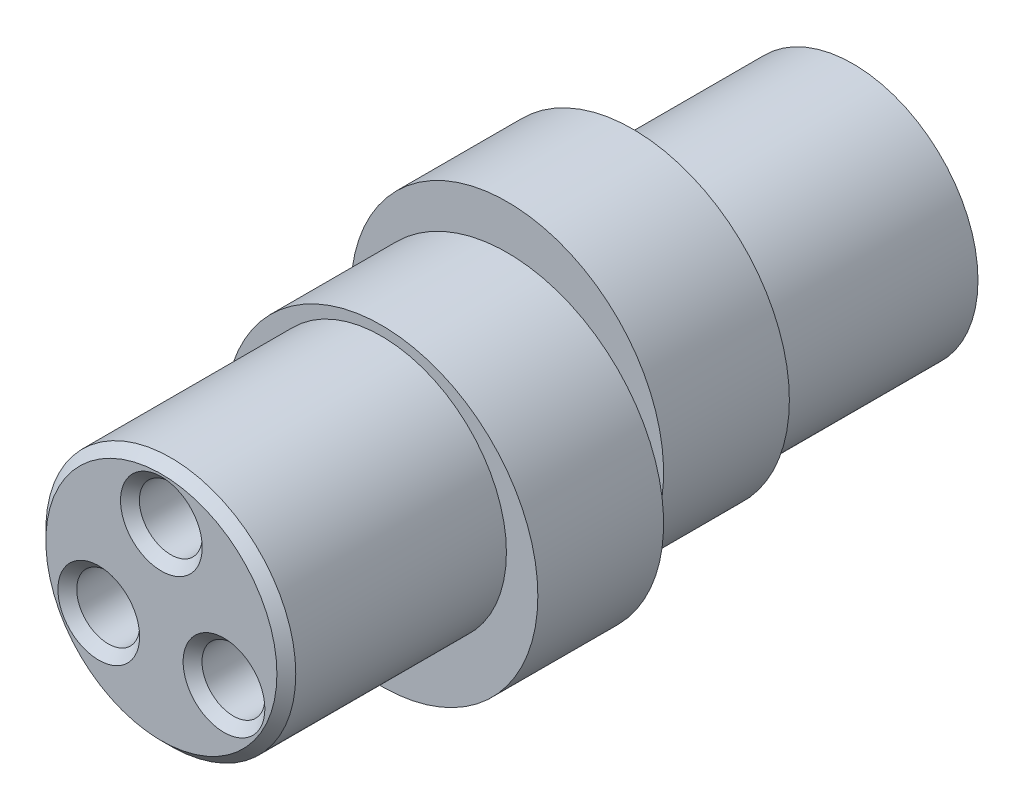
SolidWorks part; units mm, degrees
ref_plane "Front Plane" through (0, 0, 0) normal (0, 0, 1) x (1, 0, 0)
ref_plane "Top Plane" through (0, 0, 0) normal (0, 1, 0) x (1, 0, 0)
ref_plane "Right Plane" through (0, 0, 0) normal (1, 0, 0) x (0, 0, -1)
sketch "Sketch1" plane through (0, 0, 0) normal (0, 0, 1) x (1, 0, 0)
  circle A2 centre (0, 0.7) radius 4.975
  dimension "D1" = 9.95
  dimension "D2" = 0.7
extrude "Boss-Extrude1" add sketch "Sketch1" along normal blind 4 contours A2
sketch "Sketch2" plane through (0, 0, 0) normal (0, 0, 1) x (1, 0, 0)
  circle A0 centre (0, -0.7) radius 4.975
  dimension "D2" = 0.7
  dimension "D1" = 9.95
extrude "Boss-Extrude2" add sketch "Sketch2" along normal blind 4 from surface at 4 starting at face at (4.975, 0.7, 4)
sketch "Sketch5" plane through (0, 0, 0) normal (0, 0, 1) x (1, 0, 0)
  circle A1 centre (0, 0) radius 3.975
  point P13 (0, 0)
  dimension "D2" = 7.95
extrude "Boss-Extrude5" add sketch "Sketch5" against normal blind 7 and the other way blind 15
sketch "Sketch7" plane through (0, 0, 0) normal (0, 0, 1) x (1, 0, 0)
  circle A0 centre (0, -0.7) radius 4.975
  circle A1 centre (0, -0.7) radius 5.975
  dimension "D2" = 0.7
  dimension "D1" = 9.95
  dimension "D3" = 11.95
sketch "Sketch8" plane through (0, 0, 0) normal (0, 0, 1) x (1, 0, 0)
  circle A0 centre (0, 0.7) radius 4.975
  circle A1 centre (0, 0.7) radius 5.975
  dimension "D1" = 11.95
  dimension "D2" = 9.95
  dimension "D3" = 0.7
sketch "Sketch9" plane through (0, 0, 0) normal (0, 0, 1) x (1, 0, 0)
  line L0 (0, 0) -> (0, 3.5226) construction
  circle A1 centre (0, 2.3) radius 1
  circle A2 centre (1.9919, -1.15) radius 1
  circle A3 centre (-1.9919, -1.15) radius 1
  point P12 (0, 0)
  dimension "D1" = 2
  dimension "D2" = 2.3
  dimension "D3" = 3
extrude "Cut-Extrude1" cut sketch "Sketch9" against normal through all and the other way through all contours A1 L0 | L0 A1 | A3 | A2
sketch "Sketch10" plane through (0, 0, 0) normal (0, 0, 1) x (1, 0, 0)
  circle A0 centre (0, 0) radius 6
  dimension "D1" = 12
chamfer "Chamfer1" distance 0.3 angle 45 4 edges at (3.975, 0, 15) (2.9919, -1.15, 15) (-0.9919, -1.15, 15) (1, 2.3, 15)
equation "\"d1\"= 0.7"
equation "\"d2\"=9.95"
equation "\"d3\"=7"
equation "\"D1@Sketch1\"= \"d2\""
equation "\"D2@Sketch1\"=\"d1\""
equation "\"D1@Sketch2\" = \"d2\""
equation "\"D2@Sketch2\" = \"d1\""
equation "\"d4\"=4"
equation "\"D2@Sketch7\"=\"d1\""
equation "\"D1@Sketch7\"=\"d2\""
equation "\"D3@Sketch7\"=\"d2\"+2"
equation "\"D1@Sketch8\"=\"d2\"+2"
equation "\"D2@Sketch8\"=\"d2\""
equation "\"D3@Sketch8\"=\"d1\""
equation "\"D1@Boss-Extrude2\"=\"d4\""
equation "\"D1@Boss-Extrude1\"=\"d4\""
